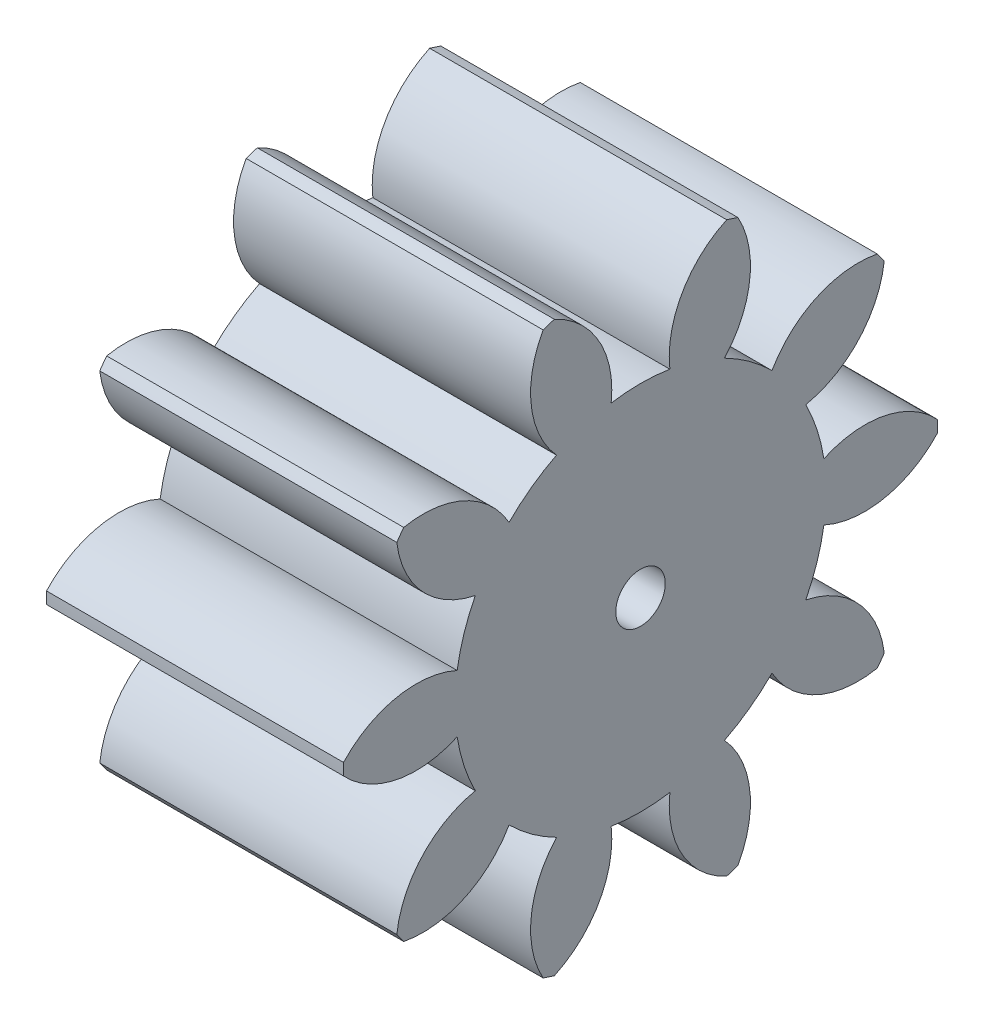
SolidWorks part; units mm, degrees
ref_plane "Plane1" through (0, 0, 0) normal (0, 0, 1) x (1, 0, 0)
ref_plane "Plane2" through (0, 0, 0) normal (0, 1, 0) x (1, 0, 0)
ref_plane "Plane3" through (0, 0, 0) normal (1, 0, 0) x (0, 0, -1)
other "Configuration Table"
sketch "HoldingSke" plane through (0, 0, 0) normal (0, 1, 0) x (1, 0, 0)
  line L0 (0, 0) -> (0.9848, -0.1736)
  line L1 (-15, 0) -> (100, 0) construction
  line L2 (0, 0) -> (-2.1039, 2.3779)
  line L3 (0, 0) -> (-11.863, 4.5341)
  line L4 (0, 0) -> (8.5048, 1.4996)
  line L5 (0, 0) -> (-46.8476, -17.4728)
  line L6 (0, 0) -> (-4.9738, -3.3558)
  line L7 (-2.1039, 2.3779) -> (8.6586, 51.2059)
  line L8 (-76.2, 54.61) -> (-76.1, 54.61)
  line L9 (-71.009, 38.7566) -> (-53.1078, 45.2721)
  line L10 (-76.2, 71.12) -> (104.1128, 71.12)
  line L11 (0, 0) -> (-6, 0)
  line L12 (-76.2, 101.6) -> (-76.162, 101.6)
  line L13 (24.9733, 27.94) -> (52.9518, 28.4284)
  line L14 (24.9733, 27.94) -> (24.9743, 27.94)
  line L15 (24.9733, 27.94) -> (100.4006, 29.5858)
  line L16 (-63.627, -1) -> (-12.827, -1)
  circle A0 centre (0, 0) radius 0.5
  circle A1 centre (0, 0) radius 3.749
  circle A2 centre (0, 0) radius 37.5
  circle A3 centre (0, 0) radius 0.5
  dimension "MHD" = 7.498
  dimension "Hub_dia" = 75
  dimension "Bore" = 1
  dimension "MBD" = 1
  dimension "Num_teeth" = 10
  dimension "Pitch" = 1
  dimension "Overall_len" = 50
  dimension "Show_teeth" = 10
  dimension "Thickness" = 6
  dimension "OAL" = 50.0001
  dimension "T_dim" = 0.1
  dimension "Ap" = 20
  dimension "H" = 19.05
  dimension "Pitch_radius" = 180.3128
  dimension "Width" = 6
  dimension "Backlash" = 0.038
  dimension "Addendum_fac" = 1
  dimension "Dedendum_fac" = 1.25
  dimension "Clearance_fac" = 0.25
  dimension "Dedendum_add" = 0.001
  dimension "Module" = 1
sketch "BasProSke" plane through (0, 0, 0) normal (0, 1, 0) x (1, 0, 0)
  line L0 (-10, 0) -> (60, 0) construction
  line L1 (0, 0) -> (0, 6)
  line L2 (0, 0) -> (6, 0)
  line L3 (6, 0) -> (6, 6)
  line L4 (6, 6) -> (0, 6)
  dimension "Thickness" = 6
  dimension "Diameter" = 12
revolve "Base-Revolve" add sketch "BasProSke" angle 360 about L0
sketch "TooCutSke" plane through (0, 0, 0) normal (1, 0, 0) x (0, 0, -1)
  line L1 (0, 0) -> (0, 107) construction
  line L2 (0, 0) -> (-0.8485, 4.9275) construction
  line L3 (0, 0) -> (-3.0584, 9.4126) construction
  line L4 (-0.8485, 4.9275) -> (-1.5292, 4.7063) construction
  arc A0 (0.5928, 3.7018) -> (-0.5928, 3.7018) centre (0, 0) ccw
  arc A1 (1.7758, 5.7578) -> (-1.7758, 5.7578) centre (0, 0) ccw
  circle A2 centre (0, 0) radius 5 construction
  circle A3 centre (0, 0) radius 4.6985 construction
  arc A4 (-0.5928, 3.7018) -> (-1.7758, 5.7578) centre (-2.5801, 3.9267) ccw
  arc A5 (1.7758, 5.7578) -> (0.5928, 3.7018) centre (2.5801, 3.9267) ccw
  dimension "Root_dia" = 7.498
  dimension "Overcut_dia" = 12.0508
  dimension "Pitch_dia" = 10
  dimension "Base_dia" = 9.3969
  dimension "Flank_rad" = 2
  dimension "Half_ang" = 18
  dimension "Half_CT" = 0.7157
extrude "ToothCut" cut sketch "TooCutSke" along normal through all
fillet "Breaks" [suppressed] radius 0.02
fillet "RootFillets" [suppressed] radius 0.251
pattern_circular "TeethCuts" count 10 every 36 about axis through (-10, 0, 0) along (1, 0, 0) of "ToothCut", "RootFillets", "Breaks"
sketch "HubNeaOneSke" plane through (0, 0, 0) normal (-1, 0, 0) x (0, 0, 1)
  circle A0 centre (0, 0) radius 3.749
  dimension "Diameter" = 7.498
extrude "HubNearOne" [suppressed] add sketch "HubNeaOneSke" along normal blind 44.0001
sketch "HubNeaBotSke" plane through (0, 0, 0) normal (-1, 0, 0) x (0, 0, 1)
  circle A0 centre (0, 0) radius 3.749
  dimension "Diameter" = 7.498
extrude "HubNearBoth" [suppressed] add sketch "HubNeaBotSke" along normal blind 22
ref_plane "FarPln" through (6, 0, 0) normal (1, 0, 0) x (0, 0, -1)
sketch "HubFarSke" plane through (6, 0, 0) normal (1, 0, 0) x (0, 0, -1)
  circle A0 centre (0, 0) radius 3.749
  dimension "Diameter" = 7.498
extrude "HubFar" [suppressed] add sketch "HubFarSke" along normal blind 22
sketch "BorSke" plane through (0, 0, 0) normal (1, 0, 0) x (0, 0, -1)
  circle A0 centre (0, 0) radius 0.5
  dimension "Diameter" = 1
extrude "Bore" cut sketch "BorSke" along normal mid plane 100.0001
sketch "KeySke" plane through (0, 0, 0) normal (1, 0, 0) x (0, 0, -1)
  line L0 (-0.05, 0) -> (-0.05, 0.6)
  line L1 (-0.05, 0.6) -> (0.05, 0.6)
  line L2 (0.05, 0.6) -> (0.05, 0)
  line L3 (0, 0) -> (0, 34) construction
  line L4 (-0.05, 0) -> (0.05, 0)
  dimension "Offset" = 0.6
  dimension "Width" = 0.1
extrude "Keyway" [suppressed] cut sketch "KeySke" along normal mid plane 100.0001
pattern_circular "Keyway2" [suppressed] count 2 every 90 about axis through (-10, 0, 0) along (1, 0, 0)
equation "' \"Module@HoldingSke\" = 6.35"
equation "' \"Num_teeth@HoldingSke\" = 12"
equation "' \"Ap@HoldingSke\" =  20"
equation "' \"Ap@HoldingSke\" = 20"
equation "' \"Width@HoldingSke\" = 0.5 * 25.4"
equation "' \"Hub_dia@HoldingSke\"= 1 * 25.4"
equation "' \"Hub_dia@HoldingSke\" = 1 * 25.4"
equation "' \"Overall_len@HoldingSke\" = 1.0 * 25.4"
equation "' \"Bore@HoldingSke\" = 0.75 * 25.4"
equation "' \"T_dim@HoldingSke\" = 0.1 * 25.4"
equation "' \"Width@KeySke\" = 0.25 * 25.4"
equation "' \"Show_teeth@HoldingSke\" = 13"
equation "' \"Backlash@HoldingSke\" = 0.009 * 25.4"
equation "' \"Addendum_fac@HoldingSke\" = 1.0"
equation "' \"Dedendum_fac@HoldingSke\" = 1.25"
equation "' \"Dedendum_add@HoldingSke\" = 0.00005 * 25.4"
equation "' \"Clearance_fac@HoldingSke\" = 0.25"
equation "\"Pitch@HoldingSke\" = 1 / \"Module@HoldingSke\""
equation "\"Overcut_dia@TooCutSke\" = (\"Num_teeth@HoldingSke\" + 2 * \"Addendum_fac@HoldingSke\") / \"Pitch@HoldingSke\" + 0.002 * 25.4"
equation "\"Pitch_dia@TooCutSke\" = \"Num_teeth@HoldingSke\" / \"Pitch@HoldingSke\""
equation "\"Base_dia@TooCutSke\" = \"Num_teeth@HoldingSke\" / \"Pitch@HoldingSke\" * cos((\"Ap@HoldingSke\"  * 3.14159265 / 180))"
equation "\"Root_dia@TooCutSke\" = (\"Num_teeth@HoldingSke\" + 2) / \"Pitch@HoldingSke\" - 2 * (\"Addendum_fac@HoldingSke\" + \"Dedendum_fac@HoldingSke\") / \"Pitch@HoldingSke\" - \"Dedendum_add@HoldingSke\" * 2"
equation "\"Half_ang@TooCutSke\" = 180 / \"Num_teeth@HoldingSke\""
equation "\"Half_CT@TooCutSke\" = \"Num_teeth@HoldingSke\" / \"Pitch@HoldingSke\" * sin((3.14159265 / 2 / \"Num_teeth@HoldingSke\")) / 2 - 7 * \"Backlash@HoldingSke\" / 4"
equation "\"Flank_rad@TooCutSke\" = \"Num_teeth@HoldingSke\" / \"Pitch@HoldingSke\" / 5"
equation "\"Radius@RootFillets\" = \"Clearance_fac@HoldingSke\" / \"Pitch@HoldingSke\" + \"Dedendum_add@HoldingSke\""
equation "\"Break_rad@Breaks\" = 0.02 / \"Pitch@HoldingSke\""
equation "\"Thickness@HoldingSke\" = \"Width@HoldingSke\""
equation "\"OAL@HoldingSke\" = \"Thickness@HoldingSke\""
equation "\"MHD@HoldingSke\" = (\"Num_teeth@HoldingSke\" + 2) / \"Pitch@HoldingSke\" - 2 * (\"Addendum_fac@HoldingSke\" + \"Dedendum_fac@HoldingSke\")  / \"Pitch@HoldingSke\" - \"Dedendum_add@HoldingSke\" * 2"
equation "\"MBD@HoldingSke\" = (\"Num_teeth@HoldingSke\" + 2) / \"Pitch@HoldingSke\" - 2 * (\"Addendum_fac@HoldingSke\" + \"Dedendum_fac@HoldingSke\")  / \"Pitch@HoldingSke\" - \"Dedendum_add@HoldingSke\" * 2 - 0.002 * 25.4"
equation "\"MHD@HoldingSke\" = ((sgn( \"MHD@HoldingSke\" - \"Hub_dia@HoldingSke\" )-1)*( \"MHD@HoldingSke\" - \"Hub_dia@HoldingSke\" ))/-2+ \"Hub_dia@HoldingSke\""
equation "\"MBD@HoldingSke\" = ((sgn( \"MBD@HoldingSke\" - \"Bore@HoldingSke\" )-1)*( \"MBD@HoldingSke\" - \"Bore@HoldingSke\" ))/-2+ \"Bore@HoldingSke\""
equation "\"OAL@HoldingSke\" = ((sgn( \"OAL@HoldingSke\" - \"Overall_len@HoldingSke\" )+1)*( \"OAL@HoldingSke\" - \"Overall_len@HoldingSke\" ))/2 + \"Overall_len@HoldingSke\" + 0.000002 * 25.4"
equation "\"Num_teeth@TeethCuts\" = int( \"Show_teeth@HoldingSke\" ) + 1"
equation "\"Num_teeth@TeethCuts\" = ((sgn( \"Num_teeth@TeethCuts\" - \"Num_teeth@HoldingSke\" )-1)*( \"Num_teeth@TeethCuts\" - \"Num_teeth@HoldingSke\" ))/-2+ \"Num_teeth@HoldingSke\""
equation "\"Num_teeth@TeethCuts\" = ((sgn( \"Num_teeth@TeethCuts\" - 2.0)+1)*( \"Num_teeth@TeethCuts\" - 2.0))/2 +2.0"
equation "\"Angle@TeethCuts\" = 360.0 / \"Num_teeth@HoldingSke\""
equation "\"Diameter@BasProSke\" = (\"Num_teeth@HoldingSke\" + 2 * \"Addendum_fac@HoldingSke\") / \"Pitch@HoldingSke\""
equation "\"Thickness@BasProSke\"  = \"Thickness@HoldingSke\""
equation "' \"Fillet_rad@BasProSke\" =  \"Thickness@HoldingSke\" * 0.05"
equation "' \"Fillet_rad@BasProSke\" = \"Thickness@HoldingSke\" * 0.05"
equation "\"MHD@HoldingSke\" = ((sgn( \"MHD@HoldingSke\" - \"Root_dia@TooCutSke\" )-1)*( \"MHD@HoldingSke\" - \"Root_dia@TooCutSke\" ))/-2+ \"Root_dia@TooCutSke\""
equation "\"Diameter@HubNeaOneSke\" = \"MHD@HoldingSke\""
equation "\"Length@HubNearOne\" = \"OAL@HoldingSke\" - \"Thickness@BasProSke\""
equation "\"Diameter@HubNeaBotSke\" = \"MHD@HoldingSke\""
equation "\"Length@HubNearBoth\" = ( \"OAL@HoldingSke\" - \"Thickness@BasProSke\" ) / 2.0"
equation "\"Thickness@FarPln\" = \"Thickness@BasProSke\""
equation "\"Diameter@HubFarSke\" = \"MHD@HoldingSke\""
equation "\"Length@HubFar\" = ( \"OAL@HoldingSke\" - \"Thickness@BasProSke\" ) / 2.0"
equation "\"Diameter@BorSke\" = \"MBD@HoldingSke\""
equation "\"D1@Bore\" = \"OAL@HoldingSke\" * 2.0"
equation "\"D1@Keyway\" = \"OAL@HoldingSke\" * 2.0"
equation "\"Offset@KeySke\" = \"T_dim@HoldingSke\" + \"MBD@HoldingSke\" / 2.0"
